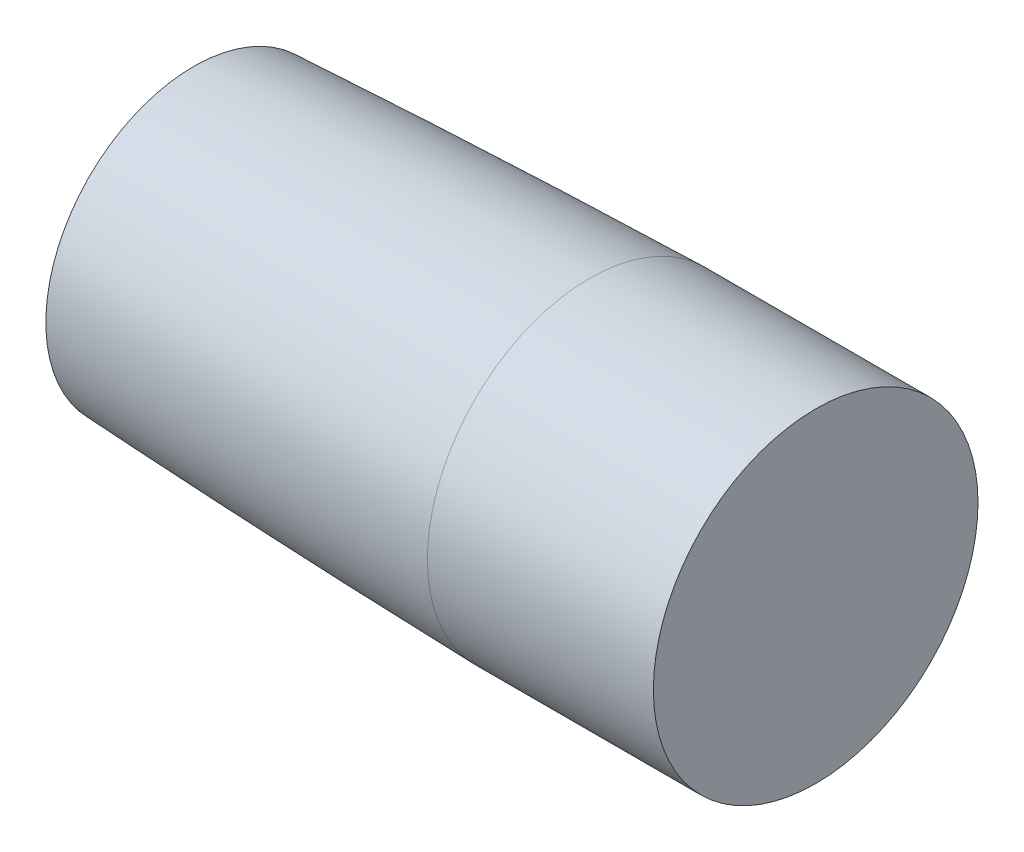
SolidWorks part; units mm, degrees
ref_plane "Front Plane" through (0, 0, 0) normal (0, 0, 1) x (1, 0, 0)
ref_plane "Top Plane" through (0, 0, 0) normal (0, 1, 0) x (1, 0, 0)
ref_plane "Right Plane" through (0, 0, 0) normal (1, 0, 0) x (0, 0, -1)
sketch "Sketch1" plane through (0, 0, 0) normal (0, 1, 0) x (1, 0, 0)
  line L0 (372.4, 44.2733) -> (372.4, 0)
  line L1 (490.97, 48.6046) -> (558.67, 48.6046)
  line L2 (558.67, 48.6046) -> (558.67, 0)
  line L3 (558.67, 0) -> (372.4, 0)
  spline S0 degree 4 poles (360.5413, 43.6674) (361.4311, 43.7137) (363.1505, 43.8029) (365.0659, 43.9041) (370.8829, 44.198) (373.0698, 44.3074) (378.9475, 44.5956) (382.3387, 44.7567) (386.7935, 44.967) (390.6626, 45.1444) (395.6093, 45.3682) (401.3939, 45.6222) (408.3122, 45.917) (416.1851, 46.2379) (424.3361, 46.5563) (432.5048, 46.8598) (440.6158, 47.1478) (448.8413, 47.4237) (456.8671, 47.6805) (465.2386, 47.9307) (472.357, 48.1337) (479.3993, 48.3196) (484.0342, 48.4386) (489.7175, 48.5756) (492.0902, 48.6312) (497.4136, 48.7521) (499.6102, 48.7982) (501.8491, 48.8457) (502.8706, 48.8669) knots 0 0 0 0 0 0.02078 0.041561 0.082618 0.111285 0.139951 0.168618 0.197284 0.225951 0.254617 0.304731 0.362064 0.419398 0.476731 0.534064 0.591397 0.64873 0.706063 0.763396 0.820729 0.859303 0.887969 0.916636 0.944257 0.971877 1 1 1 1 1 construction
  spline S1 degree 4 poles (372.4, 44.2733) (373.2493, 44.3156) (374.9691, 44.4005) (378.9475, 44.5956) (382.3387, 44.7567) (386.7935, 44.967) (390.6626, 45.1444) (395.6093, 45.3682) (401.3939, 45.6222) (408.3122, 45.917) (416.1851, 46.2379) (424.3361, 46.5563) (432.5048, 46.8598) (440.6158, 47.1478) (448.8413, 47.4237) (456.8671, 47.6805) (465.2386, 47.9307) (472.357, 48.1337) (479.3993, 48.3196) (484.0342, 48.4386) (488.4468, 48.545) (490.1199, 48.5847) (490.97, 48.6046) knots 0.082618 0.082618 0.082618 0.082618 0.082618 0.111285 0.139951 0.168618 0.197284 0.225951 0.254617 0.304731 0.362064 0.419398 0.476731 0.534064 0.591397 0.64873 0.706063 0.763396 0.820729 0.859303 0.887969 0.916636 0.916636 0.916636 0.916636 0.916636
revolve "Revolve1" add sketch "Sketch1" angle 360 about L3
sketch "Sketch2" plane through (372.4, 0, 0) normal (-1, 0, 0) x (0, 0, 1)
  circle A0 centre (0, 0) radius 12.7
extrude "Cut-Extrude1" cut sketch "Sketch2" against normal blind 50.8
